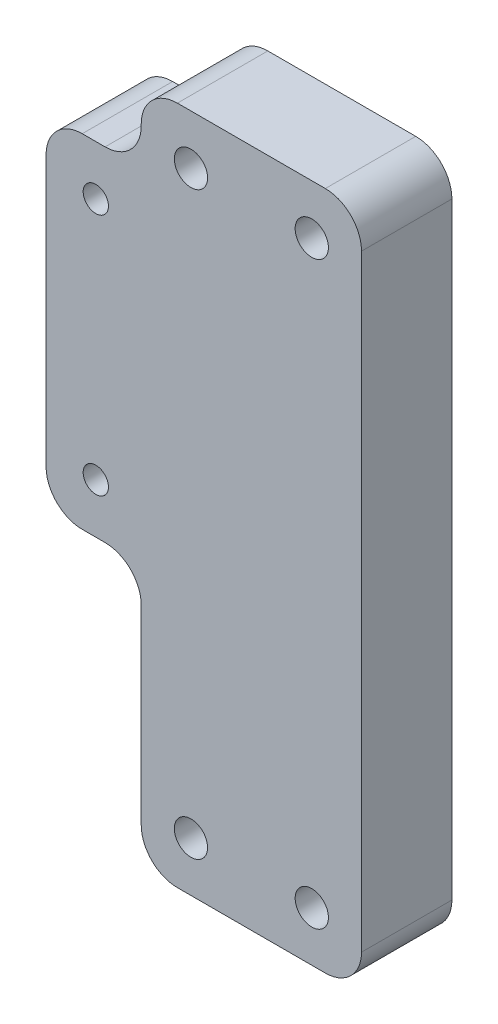
SolidWorks part; units mm, degrees
ref_plane "Front Plane" through (0, 0, 0) normal (0, 0, 1) x (1, 0, 0)
ref_plane "Top Plane" through (0, 0, 0) normal (0, 1, 0) x (1, 0, 0)
ref_plane "Right Plane" through (0, 0, 0) normal (1, 0, 0) x (0, 0, -1)
sketch "Sketch1" plane through (0, 0, 0) normal (0, 0, 1) x (1, 0, 0)
  line L0 (-31.4532, -3.5825) -> (-31.4532, -46.2225)
  line L1 (-44.3832, -1.0425) -> (-33.9932, -1.0425)
  line L2 (-53.6057, -8.7842) -> (-53.6057, -27.7707)
  line L3 (-44.3832, -48.7625) -> (-33.9932, -48.7625)
  line L9 (-51.0657, -6.2442) -> (-49.4632, -6.2442)
  line L10 (-46.9232, -3.5825) -> (-46.9232, -3.7042)
  line L11 (-46.9232, -46.2225) -> (-46.9232, -32.8507)
  line L13 (-49.4632, -30.3107) -> (-51.0657, -30.3107)
  circle A0 centre (-43.4307, -4.535) radius 1.1684
  circle A1 centre (-34.9457, -4.535) radius 1.1684
  circle A2 centre (-43.4307, -45.27) radius 1.1684
  circle A3 centre (-34.9457, -45.27) radius 1.1684
  arc A4 (-31.4532, -3.5825) -> (-33.9932, -1.0425) centre (-33.9932, -3.5825) ccw
  arc A5 (-44.3832, -1.0425) -> (-46.9232, -3.5825) centre (-44.3832, -3.5825) ccw
  arc A6 (-31.4532, -46.2225) -> (-33.9932, -48.7625) centre (-33.9932, -46.2225) cw
  arc A7 (-46.9232, -46.2225) -> (-44.3832, -48.7625) centre (-44.3832, -46.2225) ccw
  circle A8 centre (-50.1132, -9.7367) radius 0.889
  circle A9 centre (-50.1132, -26.8182) radius 0.889
  arc A10 (-46.9232, -32.8507) -> (-49.4632, -30.3107) centre (-49.4632, -32.8507) ccw
  arc A11 (-53.6057, -27.7707) -> (-51.0657, -30.3107) centre (-51.0657, -27.7707) ccw
  arc A12 (-46.9232, -3.7042) -> (-49.4632, -6.2442) centre (-49.4632, -3.7042) cw
  arc A13 (-53.6057, -8.7842) -> (-51.0657, -6.2442) centre (-51.0657, -8.7842) cw
  dimension "D7" = 2.3368
  dimension "D8" = 2.3368
  dimension "D9" = 2.3368
  dimension "D10" = 2.3368
  dimension "D11" = 3.4925
  dimension "D12" = 17.0815
  dimension "D13" = 3.4925
  dimension "D14" = 3.4925
  dimension "D15" = 3.4925
  dimension "D16" = 3.4925
  dimension "D17" = 3.4925
  dimension "D19" = 2.54
  dimension "D23" = 2.54
  dimension "D25" = 3.4925
  dimension "D3" = 1.778
  dimension "D4" = 1.778
  dimension "D22" = 3.4925
extrude "Boss-Extrude1" add sketch "Sketch1" along normal blind 6.35
